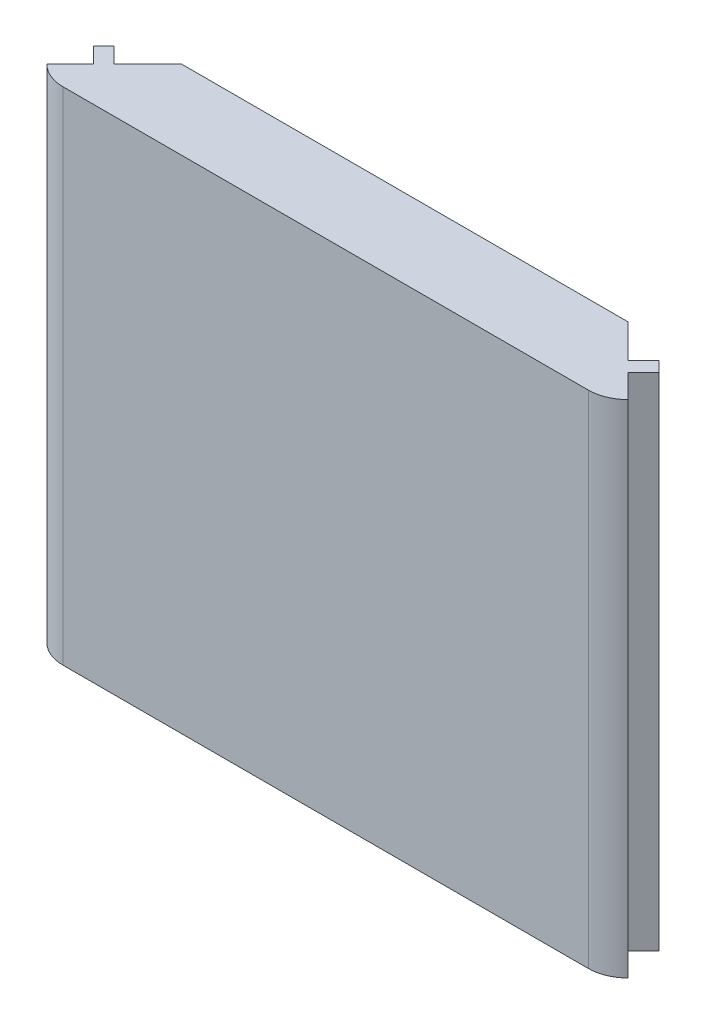
SolidWorks part; units mm, degrees
material "ПК/АБС"
ref_plane "Спереди" through (0, 0, 0) normal (0, 0, 1) x (1, 0, 0)
ref_plane "Сверху" through (0, 0, 0) normal (0, 1, 0) x (1, 0, 0)
ref_plane "Справа" through (0, 0, 0) normal (1, 0, 0) x (0, 0, -1)
sketch "Эскиз1" plane through (0, 0, 0) normal (0, 0, 1) x (1, 0, 0)
  line L1 (-40.95, 33.95) -> (40.95, 33.95)
  line L2 (-40.95, 33.95) -> (-40.95, -33.95)
  line L3 (-40.95, -33.95) -> (40.95, -33.95)
  line L4 (40.95, 33.95) -> (40.95, -33.95)
  point P0 (0, 0)
extrude "Бобышка-Вытянуть1" add sketch "Эскиз1" against normal blind 10.7
sketch "Эскиз2" plane through (0, 0, -10.7) normal (0, 0, -1) x (-1, 0, 0)
  line L1 (-30.25, 30.25) -> (30.25, 30.25)
  line L2 (-30.25, 30.25) -> (-30.25, -30.25)
  line L3 (-30.25, -30.25) -> (30.25, -30.25)
  line L4 (30.25, 30.25) -> (30.25, -30.25)
  line L5 (-30.25, 30.25) -> (30.25, -30.25) construction
  line L6 (-30.25, -30.25) -> (30.25, 30.25) construction
  point P0 (0, 0)
extrude "Вырез-Вытянуть1" cut sketch "Эскиз2" against normal blind 9.2
sketch "Эскиз3" plane through (0, 33.95, 0) normal (0, 1, 0) x (1, 0, 0)
  line L0 (-40.95, 0) -> (-30.25, 10.7)
  line L1 (-30.25, 10.7) -> (-40.95, 10.7)
  line L2 (-40.95, 10.7) -> (-40.95, 0)
  line L4 (40.95, 10.7) -> (40.95, 0)
  line L5 (30.25, 10.7) -> (40.95, 10.7)
  line L6 (40.95, 0) -> (30.25, 10.7)
extrude "Вырез-Вытянуть2" cut sketch "Эскиз3" against normal up to next
sketch "Эскиз4" plane through (0, -33.95, -40.95) normal (0, 1, 0) x (1, 0, 0)
  line L2 (39.383, -39.383) -> (40.95, -40.95)
  line L3 (40.95, -40.95) -> (35.6, -40.95)
  line L4 (-40.95, -40.95) -> (-35.6, -40.95)
  line L5 (-39.383, -39.383) -> (-40.95, -40.95)
  arc A0 (35.6, -40.95) -> (39.383, -39.383) centre (35.6, -35.6) ccw
  arc A1 (-35.6, -40.95) -> (-39.383, -39.383) centre (-35.6, -35.6) cw
  point P0 (-40.95, -40.95)
extrude "Вырез-Вытянуть4" cut sketch "Эскиз4" along normal up to next
sketch "Эскиз7" plane through (0, 33.95, 0) normal (0, 1, 0) x (1, 0, 0)
  line L0 (-38.352, 6.8406) -> (-36.9378, 8.2548)
  line L2 (36.9378, 8.2548) -> (34.8165, 6.1335)
  line L3 (34.8165, 6.1335) -> (36.2307, 4.7193)
  line L4 (36.2307, 4.7193) -> (38.352, 6.8406)
  line L5 (38.352, 6.8406) -> (36.9378, 8.2548)
  line L8 (-36.2307, 4.7193) -> (-38.352, 6.8406)
  line L9 (-34.8165, 6.1335) -> (-36.2307, 4.7193)
  line L10 (-36.9378, 8.2548) -> (-34.8165, 6.1335)
extrude "Бобышка-Вытянуть2" add sketch "Эскиз7" against normal up to surface (67.9 mm away) up to face at (0, -33.95, -3.9636)
